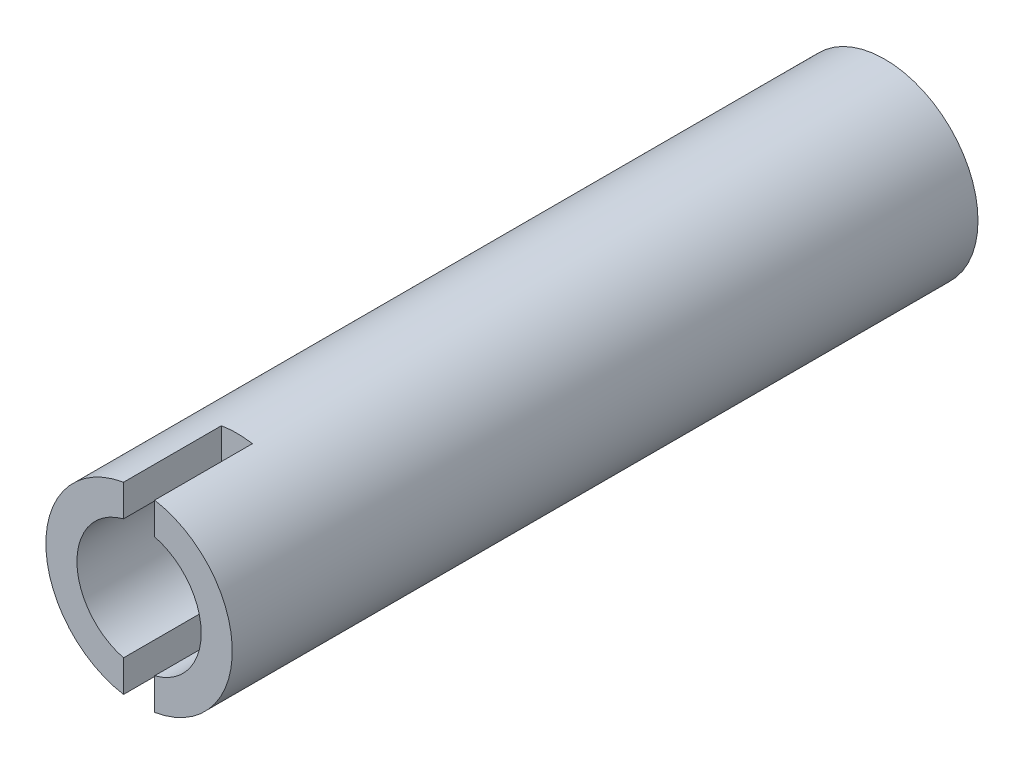
SolidWorks part; units mm, degrees
material "6061-T6 (SS)"
ref_plane "Front" through (0, 0, 0) normal (0, 0, 1) x (1, 0, 0)
ref_plane "Top" through (0, 0, 0) normal (0, 1, 0) x (1, 0, 0)
ref_plane "Right" through (0, 0, 0) normal (1, 0, 0) x (0, 0, -1)
sketch "Sketch1" plane through (0, 0, 0) normal (0, 0, 1) x (1, 0, 0)
  circle A0 centre (0, 0) radius 9.525
  circle A1 centre (0, 0) radius 6.35
  dimension "D1" = 19.05
  dimension "D2" = 12.7
extrude "Boss-Extrude1" add sketch "Sketch1" along normal blind 76.2
sketch "Sketch2" plane through (0, 0, 76.2) normal (0, 0, 1) x (1, 0, 0)
  line L1 (-1.5875, 12.5895) -> (1.5875, 12.5895)
  line L2 (-1.5875, 12.5895) -> (-1.5875, -12.5895)
  line L3 (-1.5875, -12.5895) -> (1.5875, -12.5895)
  line L4 (1.5875, 12.5895) -> (1.5875, -12.5895)
  line L5 (-1.5875, 12.5895) -> (1.5875, -12.5895) construction
  line L6 (-1.5875, -12.5895) -> (1.5875, 12.5895) construction
  point P0 (0, 0)
  dimension "D1" = 3.175
extrude "Cut-Extrude1" cut sketch "Sketch2" against normal blind 10
sketch "Sketch3" plane through (0, 0, 0) normal (1, 0, 0) x (0, 0, -1)
  circle A0 centre (-8.89, 0) radius 3.2639
  dimension "D2" = 6.5278
  dimension "D1" = 8.89
extrude "Cut-Extrude2" [suppressed] cut sketch "Sketch3" against normal mid plane 50
